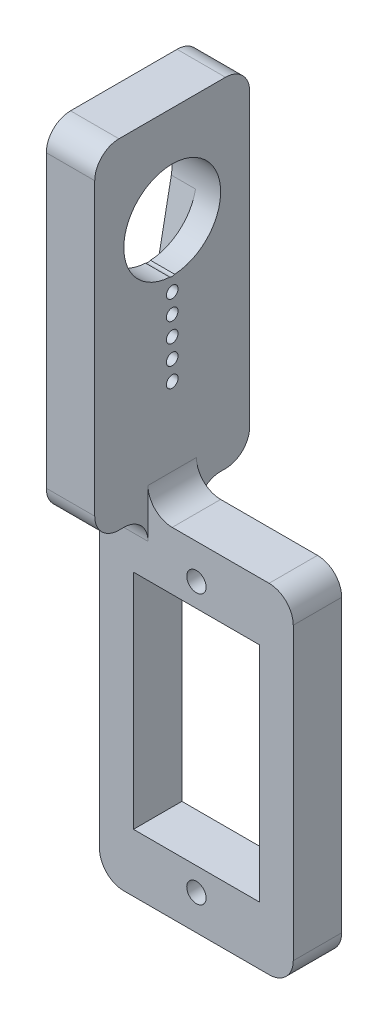
SolidWorks part; units mm, degrees
ref_plane "前视基准面" through (0, 0, 0) normal (0, 0, 1) x (1, 0, 0)
ref_plane "上视基准面" through (0, 0, 0) normal (0, 1, 0) x (1, 0, 0)
ref_plane "右视基准面" through (0, 0, 0) normal (1, 0, 0) x (0, 0, -1)
other "Configuration Table"
sketch "Sketch1" plane through (0, 0, 0) normal (0, 0, 1) x (1, 0, 0)
  line L1 (-6.5, -11.5) -> (6.5, -11.5)
  line L2 (-6.5, -11.5) -> (-6.5, 11.5)
  line L3 (-6.5, 11.5) -> (6.5, 11.5)
  line L4 (6.5, -11.5) -> (6.5, 11.5)
  line L5 (-6.5, -11.5) -> (6.5, 11.5) construction
  line L6 (-6.5, 11.5) -> (6.5, -11.5) construction
  line L7 (-10, -17.5) -> (10, -17.5)
  line L8 (-10, -17.5) -> (-10, 17.5)
  line L9 (-10, 17.5) -> (10, 17.5)
  line L10 (10, -17.5) -> (10, 17.5)
  line L11 (-10, -17.5) -> (10, 17.5) construction
  line L12 (-10, 17.5) -> (10, -17.5) construction
  point P0 (0, 0)
  point P6 (0, 0)
  dimension "D1" = 13
  dimension "D2" = 23
  dimension "D3" = 20
  dimension "D4" = 35
extrude "Boss-Extrude1" add sketch "Sketch1" along normal blind 5
sketch "Sketch2" plane through (0, 0, 5) normal (0, 0, 1) x (1, 0, 0)
  line L0 (0, 0) -> (0, 13.9) construction
  line L1 (0, 0) -> (5.3694, 0) construction
  circle A0 centre (0, 13.9) radius 1
  circle A1 centre (0, -13.9) radius 1
  dimension "D2" = 2
  dimension "D1" = 13.9
extrude "Cut-Extrude1" cut sketch "Sketch2" against normal blind 5
sketch "Sketch3" plane through (-10, 0, 0) normal (-1, 0, 0) x (0, 0, 1)
  line L0 (2.5, 17.5) -> (2.5, 30.9217) construction
  line L1 (5, 17.5) -> (0, 17.5) construction
  line L2 (-5.5, 17.5) -> (10.5, 17.5)
  line L3 (10.5, 17.5) -> (10.5, 52.5)
  line L4 (10.5, 52.5) -> (-5.5, 52.5)
  line L5 (2.5, 52.5) -> (2.5, 17.5)
  line L6 (-5.5, 17.5) -> (-5.5, 52.5)
  line M8 (5, 17.5) -> (0, 17.5)
  dimension "D1" = 35
  dimension "D2" = 8
extrude "Boss-Extrude2" add sketch "Sketch3" against normal blind 5 contours L6 L2 L5 L4 | L4 L5 L2 L3 M8
fillet "Fillet1" radius 2.5 2 edges at (-7.5, 17.5, 5) (-7.5, 17.5, 0)
sketch "Sketch5" plane through (-5, 0, 0) normal (1, 0, 0) x (0, 0, -1)
  line L0 (-2.5, 17.5) -> (-2.5, 42.5) construction
  line L1 (-5, 17.5) -> (0, 17.5) construction
  circle A0 centre (-2.5, 42.5) radius 5
  dimension "D1" = 10
  dimension "D2" = 25
extrude "Cut-Extrude2" cut sketch "Sketch5" against normal blind 5 contours A0
sketch "Sketch6" plane through (-10, 0, 0) normal (-1, 0, 0) x (0, 0, 1)
  line L0 (2.5, 42.5) -> (2.5, 38.05) construction
  circle A0 centre (2.5, 38.05) radius 0.6
  circle A1 centre (2.5, 36.05) radius 0.6
  circle A2 centre (2.5, 34.05) radius 0.6
  circle A3 centre (2.5, 32.05) radius 0.6
  circle A4 centre (2.5, 30.05) radius 0.6
  circle A5 centre (2.5, 28.05) radius 0.6
  dimension "D1" = 1.2
  dimension "D2" = 4.45
  dimension "D3" = 6
extrude "Cut-Extrude3" cut sketch "Sketch6" against normal blind 5
sketch "Sketch8" plane through (-10, 0, 0) normal (-1, 0, 0) x (0, 0, 1)
  line L0 (-2.4086, 41.5484) -> (0.2911, 27.6218)
  line L1 (7.4086, 41.5484) -> (4.7089, 27.6218)
  circle A0 centre (2.5, 42.5) radius 5
  circle A1 centre (2.5, 28.05) radius 2.25
  circle M3 centre (2.5, 36.05) radius 0.6
  circle M4 centre (2.5, 34.05) radius 0.6
  circle M5 centre (2.5, 32.05) radius 0.6
  circle M6 centre (2.5, 30.05) radius 0.6
  circle M7 centre (2.5, 28.05) radius 0.6
  arc M8 (2.2459, 37.5065) -> (2.7541, 37.5065) centre (2.5, 42.5) cw
  arc M9 (2.7541, 37.5065) -> (2.2459, 37.5065) centre (2.5, 38.05) cw
  dimension "D1" = 4.5
  dimension "D2" = 10
extrude "Cut-Extrude4" cut sketch "Sketch8" against normal blind 2.5 contours A1 L1 L0 M6 M8 M9 M3 M5 M4 | A1 M6 M7 | A0 M8
fillet "Fillet2" radius 2.5 8 edges at (-7.5, 52.5, -5.5) (-7.5, 52.5, 10.5) (-7.5, 17.5, -5.5) (-7.5, 17.5, 10.5) (-5, 17.5, 2.5) (10, 17.5, 2.5) (-10, -17.5, 2.5) (10, -17.5, 2.5)
